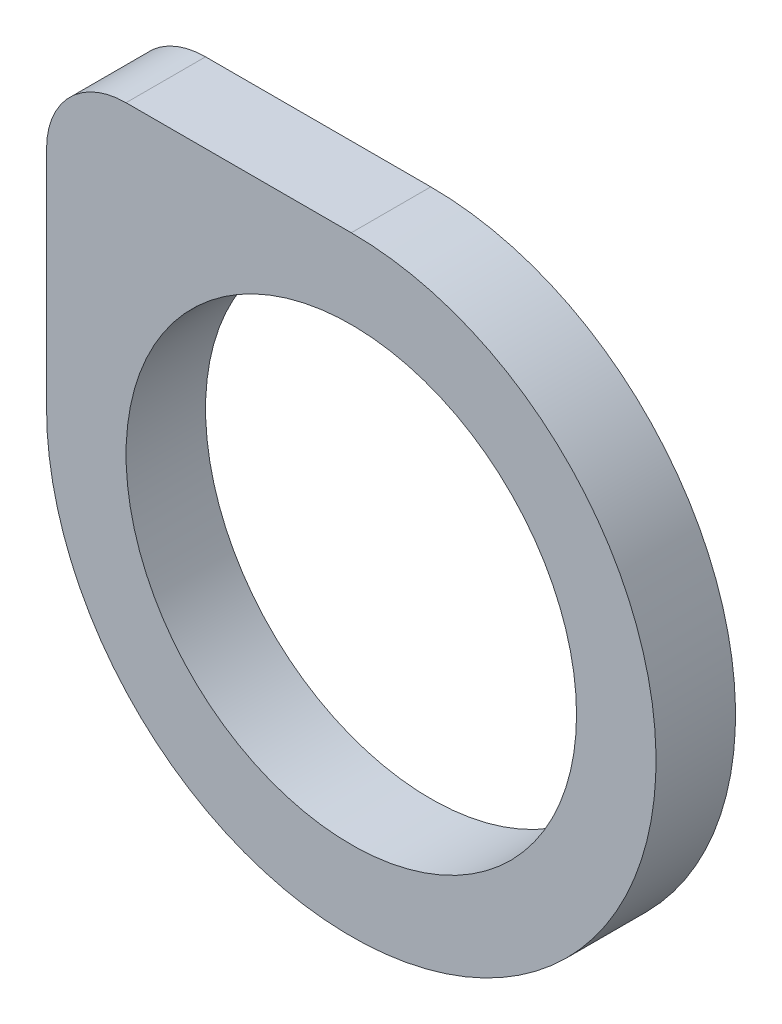
SolidWorks part; units mm, degrees
ref_plane "Front Plane" through (0, 0, 0) normal (0, 0, 1) x (1, 0, 0)
ref_plane "Top Plane" through (0, 0, 0) normal (0, 1, 0) x (1, 0, 0)
ref_plane "Right Plane" through (0, 0, 0) normal (1, 0, 0) x (0, 0, -1)
sketch "Sketch1" plane through (0, 0, 0) normal (0, 0, 1) x (1, 0, 0)
  line L0 (-11.5, 0) -> (-11.5, 8.5)
  line L1 (-8.5, 11.5) -> (0, 11.5)
  circle A0 centre (0, 0) radius 8.5
  arc A1 (-11.5, 0) -> (0, 11.5) centre (0, 0) ccw
  arc A2 (-11.5, 8.5) -> (-8.5, 11.5) centre (-8.5, 8.5) cw
  dimension "D1" = 17
  dimension "D2" = 23
  dimension "D3" = 3
extrude "Boss-Extrude1" add sketch "Sketch1" along normal blind 3
